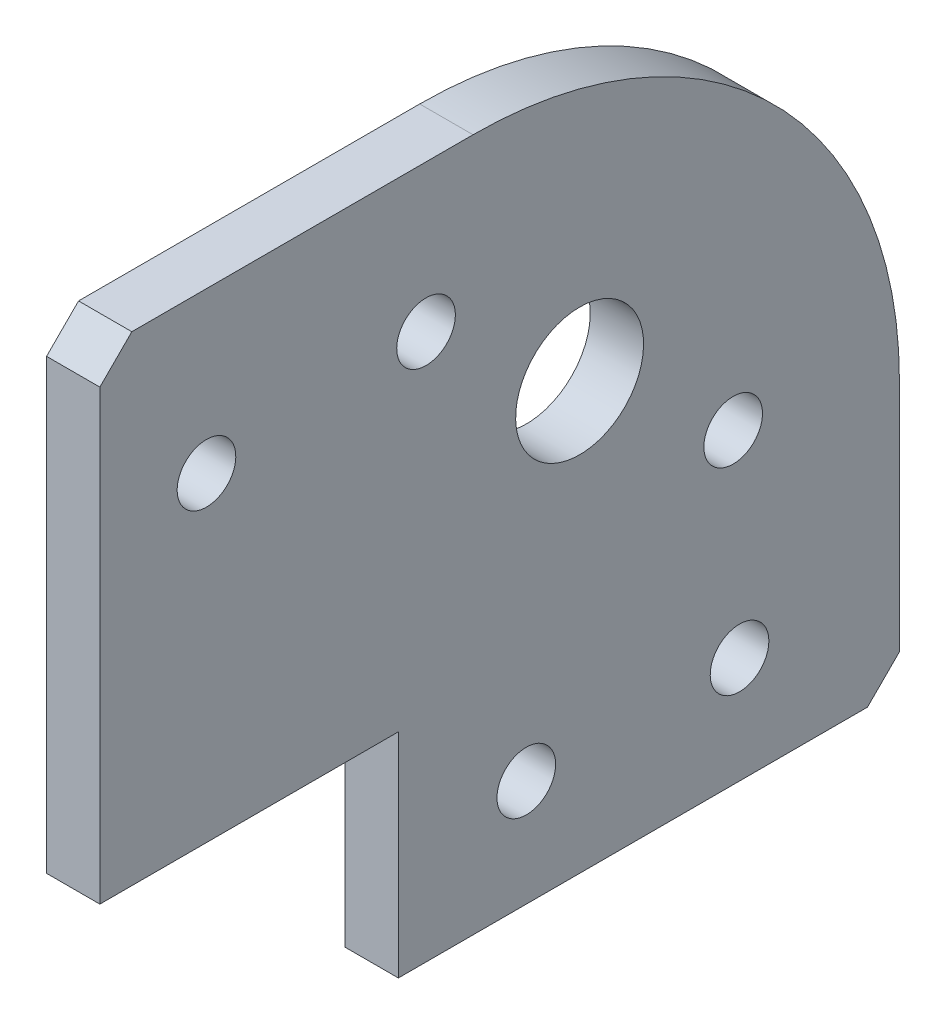
SolidWorks part; units mm, degrees
ref_plane "Front Plane" through (0, 0, 0) normal (0, 0, 1) x (1, 0, 0)
ref_plane "Top Plane" through (0, 0, 0) normal (0, 1, 0) x (1, 0, 0)
ref_plane "Right Plane" through (0, 0, 0) normal (1, 0, 0) x (0, 0, -1)
ref_plane "Plane1" through (600.8288, 0, 0) normal (-1, 0, 0) x (0, -1, 0)
sketch "Sketch1" plane through (600.8288, 0, 0) normal (-1, 0, 0) x (0, -1, 0)
  line L0 (40, 25) -> (-25, 25) construction
  line L1 (30, -40) -> (30, 35) construction
  line L6 (40, 35) -> (-25, 35)
  line L8 (-25, 35) -> (-25, -40)
  line L10 (-25, -40) -> (40, -40)
  line L12 (40, -40) -> (40, 35)
  circle A0 centre (30, -5) radius 2.75
  circle A8 centre (-10, 25) radius 2.75
  circle A11 centre (30, -25) radius 2.75
  circle A12 centre (0, -10) radius 6
  dimension "D7" = 12
  dimension "D8" = 5.5
  dimension "D9" = 5.5
  dimension "D2" = 5.5
  dimension "D3" = 75
  dimension "D4" = 65
  dimension "D5" = 30
  dimension "D6" = 40
  dimension "D10" = 10
  dimension "D11" = 50
  dimension "D12" = 10
  dimension "D13" = 60
  dimension "D14" = 20
extrude "Boss-Extrude1" add sketch "Sketch1" against normal blind 5
chamfer "Chamfer1" distance 3 angle 45 3 edges at (603.3288, -40, -40) (603.3288, -40, 35) (603.3288, 25, 35)
sketch "Sketch2" plane through (600.8288, 0, 0) normal (-1, 0, 0) x (0, 0, 1)
  line L0 (4.4057, 11.2044) -> (-24.4057, -11.2044) construction
  circle A0 centre (4.4057, 11.2044) radius 2.75
  circle A1 centre (-24.4057, -11.2044) radius 2.75
  point P4 (0, 0)
  point P10 (-10, 0)
  dimension "D1" = 5.5
  dimension "D2" = 5.5
  dimension "D3" = 18.25
  dimension "D4" = 18.25
  dimension "D5" = 52.125
extrude "Cut-Extrude1" cut sketch "Sketch2" against normal up to next
sketch "Sketch3" plane through (600.8288, 0, 0) normal (-1, 0, 0) x (0, 0, 1)
  line L0 (35, -37) -> (35, 22) construction
  line L1 (35, -20) -> (7, -20)
  line L2 (35, -20) -> (35, -40)
  line L3 (35, -40) -> (7, -40)
  line L4 (7, -20) -> (7, -40)
  line L5 (-37, -40) -> (32, -40) construction
  dimension "D1" = 20
  dimension "D2" = 28
extrude "Cut-Extrude2" cut sketch "Sketch3" against normal up to next
fillet "Fillet1" radius 40 1 edges at (603.3288, 25, -40)
